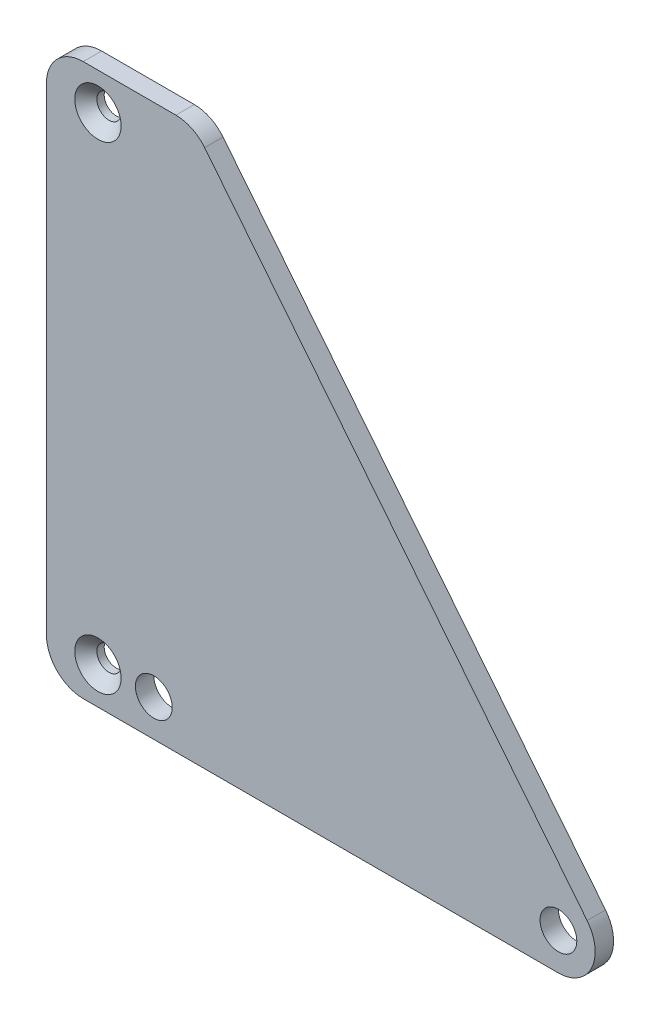
SolidWorks part; units mm, degrees
ref_plane "Спереди" through (0, 0, 0) normal (0, 0, 1) x (1, 0, 0)
ref_plane "Сверху" through (0, 0, 0) normal (0, 1, 0) x (1, 0, 0)
ref_plane "Справа" through (0, 0, 0) normal (1, 0, 0) x (0, 0, -1)
sketch "Эскиз1" plane through (0, 0, 0) normal (0, 0, 1) x (1, 0, 0)
  line L3 (0, 0) -> (160, 0)
  line L5 (0, 150) -> (0, 0)
  line L6 (0, 150) -> (40, 150)
  line L7 (40, 150) -> (160, 0)
  point P3 (90.115, 97.8102)
  point P7 (83.2026, 101.2664)
  dimension "D1" = 160
  dimension "D2" = 150
  dimension "D4" = 40
extrude "База" add sketch "Эскиз1" along normal mid plane 5
hole_wizard "Крепление-M6" positions "Эскиз3" profile "Эскиз4" countersink size "M6" standard "ISO" end condition through all
sketch "Эскиз3" plane through (0, 0, 2.5) normal (0, 0, 1) x (1, 0, 0)
  line L0 (40, 150) -> (0, 150) construction
  line L1 (0, 0) -> (160, 0) construction
  line L2 (0, 150) -> (0, 0) construction
  point P0 (14, 140)
  point P2 (14, 10)
  dimension "D1" = 10
  dimension "D2" = 10
  dimension "D3" = 14
sketch "Эскиз4" plane through (14, 140, 2.5) normal (1, 0, 0) x (0, -1, 0)
  line L0 (0, 0) -> (0, 5)
  line L1 (0, 5) -> (3.3, 5)
  line L2 (3.3, 5) -> (3.3, 3)
  line L3 (3.3, 3) -> (6.3, 0)
  line L5 (6.3, 0) -> (0, 0)
  line L6 (-3.3, 3) -> (-6.3, 0) construction
  line L11 (0, -6.35) -> (0, 107.95) construction
  dimension "Диаметр сквозного отверстия" = 6.6
  dimension "Глубина сквозного отверстия" = 5
  dimension "Диаметр передней зенковки" = 12.6
  dimension "Угол передней зенковки" = 90
fillet "Скругление1" radius 10 4 edges at (0, 0, 0) (160, 0, 0) (40, 150, 0) (0, 150, 0)
sketch "Эскиз2" plane through (0, 0, 2.5) normal (0, 0, 1) x (1, 0, 0)
  circle A2 centre (139.1938, 10) radius 5
  circle A4 centre (29.1938, 10) radius 5
  dimension "D1" = 10
  dimension "D2" = 110
extrude "Вырез-Вытянуть1" cut sketch "Эскиз2" against normal through all
